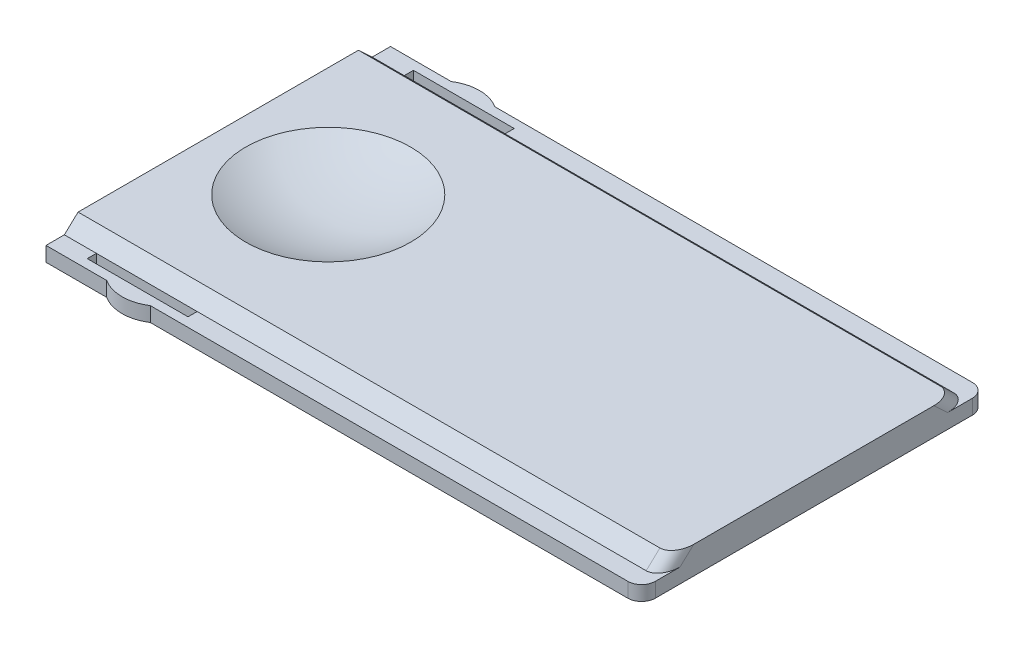
SolidWorks part; units mm, degrees
ref_plane "Front Plane" through (0, 0, 0) normal (0, 0, 1) x (1, 0, 0)
ref_plane "Top Plane" through (0, 0, 0) normal (0, 1, 0) x (1, 0, 0)
ref_plane "Right Plane" through (0, 0, 0) normal (1, 0, 0) x (0, 0, -1)
sketch "Sketch1" plane through (0, 0, 0) normal (1, 0, 0) x (0, 0, -1)
  line L0 (18.8, 0) -> (-18.8, 0)
  line L1 (-18.8, 0) -> (-18.8, 1.6)
  line L2 (-18.8, 1.6) -> (-16.8, 1.6)
  line L3 (-16.8, 1.6) -> (-15.3, 3)
  line L4 (-15.3, 3) -> (15.3, 3)
  line L5 (0, 3) -> (0, 0) construction
  line L6 (16.8, 1.6) -> (15.3, 3)
  line L7 (18.8, 1.6) -> (16.8, 1.6)
  line L8 (18.8, 0) -> (18.8, 1.6)
  point P11 (-15.6231, 3)
  dimension "D1" = 1.6
  dimension "D2" = 37.6
  dimension "D3" = 3
  dimension "D4" = 2
  dimension "D5" = 1.5
extrude "Boss-Extrude1" add sketch "Sketch1" along normal blind 65
sketch "Sketch2" plane through (0, 1.6, 0) normal (0, 1, 0) x (1, 0, 0)
  line L0 (0, 0) -> (65, 0) construction
  line L1 (65, 15.3) -> (65, -15.3) construction
  line L3 (0, 15.3) -> (0, -15.3) construction
  circle A0 centre (9, 15.1) radius 4.4
  circle A1 centre (9, -15.1) radius 4.4
  point P7 (9.5316, 19.7807)
  point P8 (9.6821, 15.6942)
  dimension "D1" = 8.8
  dimension "D2" = 15.1
  dimension "D3" = 9
extrude "Boss-Extrude-Latch" add sketch "Sketch2" against normal up to surface (1.6 mm away) up to face at (32.5, 0, 0)
sketch "Sketch3" plane through (0, 1.6, 0) normal (0, 1, 0) x (1, 0, 0)
  line L0 (65, 18.8) -> (11.3812, 18.8) construction
  line L1 (3.5, 17.8) -> (14.5, 17.8)
  line L2 (3.5, 17.8) -> (3.5, 16.8)
  line L3 (3.5, 16.8) -> (14.5, 16.8)
  line L4 (14.5, 17.8) -> (14.5, 16.8)
  line L5 (3.5, 17.8) -> (14.5, 16.8) construction
  line L6 (3.5, 16.8) -> (14.5, 17.8) construction
  line L7 (9, 19.5) -> (9, 17.3) construction
  line L9 (0, 18.8) -> (0, 16.8) construction
  line L10 (65, 16.8) -> (0, 16.8) construction
  line L11 (0, 0) -> (65, 0) construction
  line L12 (65, 15.3) -> (65, -15.3) construction
  line L13 (3.5, -16.8) -> (14.5, -16.8)
  line L14 (14.5, -17.8) -> (14.5, -16.8)
  line L15 (3.5, -17.8) -> (14.5, -17.8)
  line L16 (3.5, -17.8) -> (3.5, -16.8)
  arc A0 (11.3812, 18.8) -> (6.6188, 18.8) centre (9, 15.1) ccw construction
  point P0 (9, 17.3)
  dimension "D1" = 1
  dimension "D2" = 1
  dimension "D3" = 11
  dimension "D4" = 3.5
extrude "Cut-Extrude1" cut sketch "Sketch3" against normal through all
sketch "Sketch4" plane through (0, 0, 0) normal (0, 0, 1) x (1, 0, 0)
  line L0 (12, 39.8182) -> (12, 0.8)
  line L2 (3, 3) -> (12, 3) construction
  line L3 (65, 3) -> (0, 3) construction
  arc A0 (12, 0.8) -> (12, 39.8182) centre (12, 20.3091) cw
  dimension "D1" = 0.8
  dimension "D2" = 9
  dimension "D3" = 12
revolve "Cut-Revolve1" cut sketch "Sketch4" angle 360 about L0
fillet "Fillet1" radius 1.5 4 edges at (65, 0.8, 18.8) (65, 2.3, 16.05) (65, 2.3, -16.05) (65, 0.8, -18.8)
